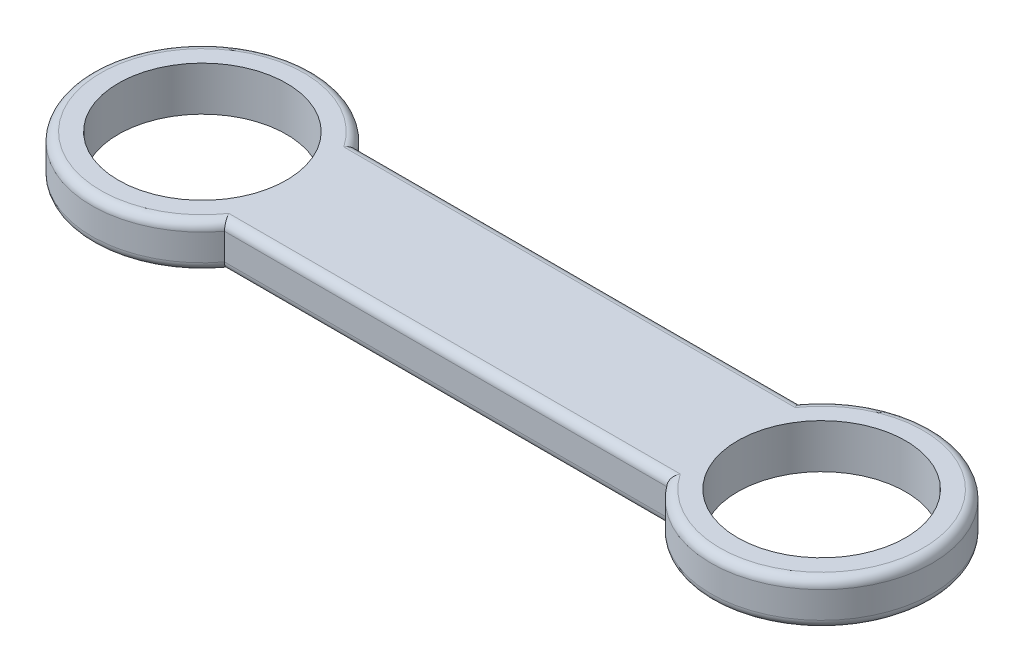
SolidWorks part; units mm, degrees
ref_plane "Front Plane" through (0, 0, 0) normal (0, 0, 1) x (1, 0, 0)
ref_plane "Top Plane" through (0, 0, 0) normal (0, 1, 0) x (1, 0, 0)
ref_plane "Right Plane" through (0, 0, 0) normal (1, 0, 0) x (0, 0, -1)
sketch "Sketch1" plane through (0, 0, 0) normal (0, 1, 0) x (1, 0, 0)
  line L0 (10, 7.5) -> (60, 7.5)
  line L1 (10, -7.5) -> (60, -7.5)
  circle A0 centre (0, 0) radius 9.5
  arc A1 (10, 7.5) -> (10, -7.5) centre (0, 0) ccw
  circle A2 centre (70, 0) radius 9.5
  arc A3 (60, -7.5) -> (60, 7.5) centre (70, 0) ccw
  point P3 (0, 0)
  dimension "D1" = 19
  dimension "D2" = 19
  dimension "D3" = 25
  dimension "D4" = 25
  dimension "D5" = 70
  dimension "D6" = 15
  dimension "D7" = 7.5
extrude "Boss-Extrude1" add sketch "Sketch1" along normal blind 5
fillet "Fillet1" radius 1 8 edges at (82.5, 0, 0) (35, 0, -7.5) (-12.5, 0, 0) (35, 0, 7.5) (82.5, 5, 0) (35, 5, -7.5) (-12.5, 5, 0) (35, 5, 7.5)
